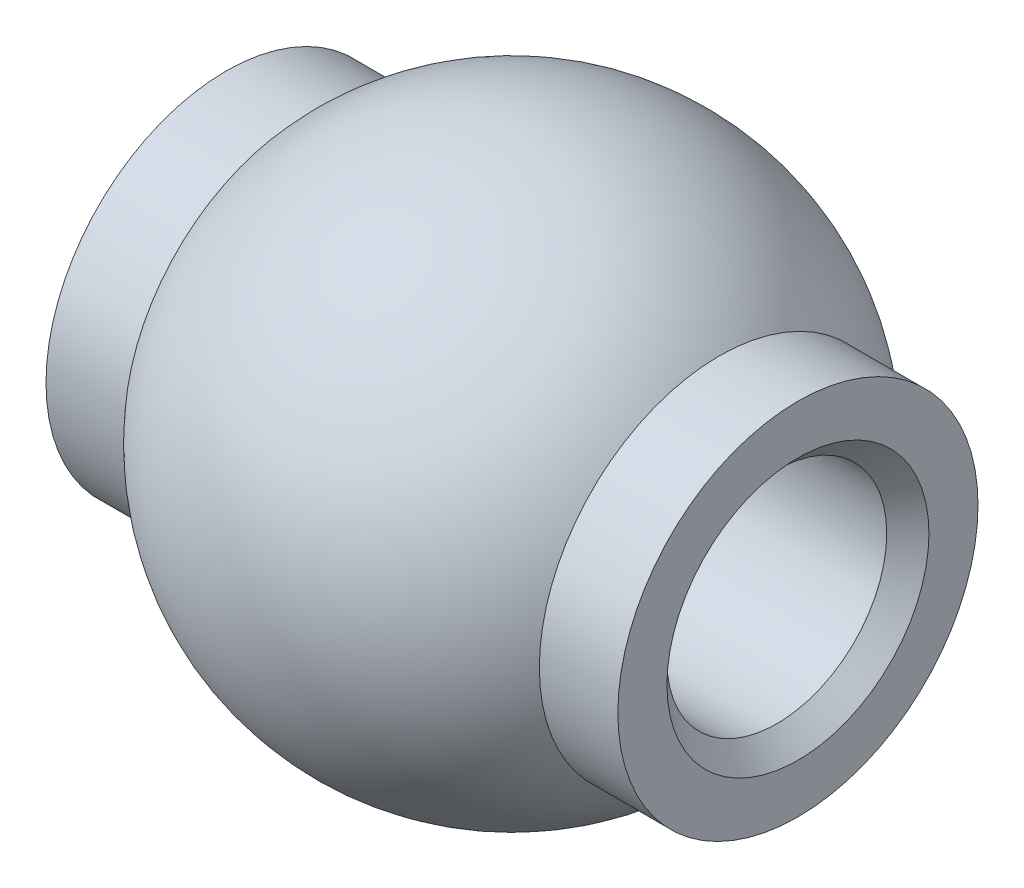
SolidWorks part; units mm, degrees
material "Alloy Steel"
ref_plane "Front Plane" through (0, 0, 0) normal (0, 0, 1) x (1, 0, 0)
ref_plane "Top Plane" through (0, 0, 0) normal (0, 1, 0) x (1, 0, 0)
ref_plane "Right Plane" through (0, 0, 0) normal (1, 0, 0) x (0, 0, -1)
sketch "Sketch1" plane through (0, 0, 0) normal (0, 0, 1) x (1, 0, 0)
  line L0 (-18.1576, 0) -> (17.6298, 0) construction
  line L1 (-10.3251, 6.5024) -> (-10.3251, 4.7307)
  line L2 (-10.3251, 6.5024) -> (-7.49, 6.5024)
  line L3 (0, 0) -> (0, 21.5223) construction
  line L4 (10.3251, 6.5024) -> (7.49, 6.5024)
  line L5 (-9.5631, 3.9688) -> (9.5631, 3.9688)
  line L6 (10.3251, 4.7307) -> (10.3251, 6.5024)
  line L9 (-10.3251, 4.7307) -> (-9.5631, 3.9688)
  line L10 (9.5631, 3.9688) -> (10.3251, 4.7307)
  arc A0 (-7.49, 6.5024) -> (7.49, 6.5024) centre (0, 0) cw
  point P4 (-10.3251, 6.5024)
  point P10 (10.3251, 6.5024)
  point P11 (-10.3251, 3.9688)
  point P12 (10.3251, 3.9688)
  dimension "D2" = 9.9187
  dimension "D1" = 20.6502
  dimension "D7" = 13.0048
  dimension "D8" = 7.9375
  dimension "D9" = 0.762
  dimension "D10" = 45
  dimension "D11" = 0.762
  dimension "D12" = 45
revolve "Revolve1" add sketch "Sketch1" angle 360 about L0
